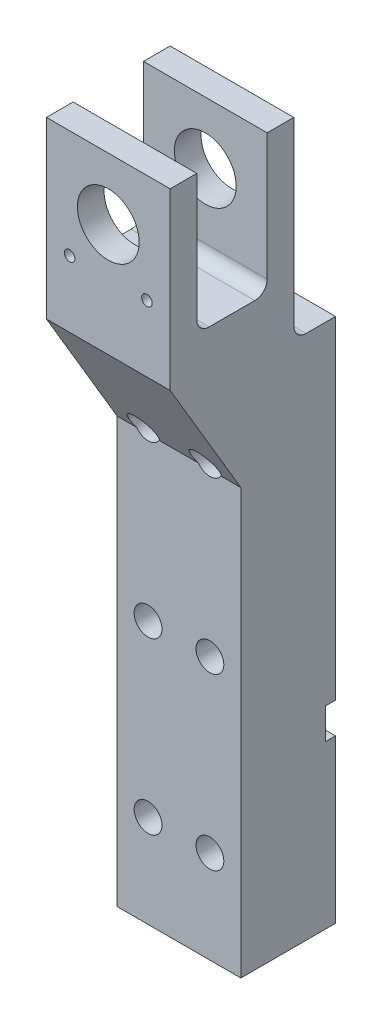
SolidWorks part; units mm, degrees
ref_plane "前视基准面" through (0, 0, 0) normal (0, 0, 1) x (1, 0, 0)
ref_plane "上视基准面" through (0, 0, 0) normal (0, 1, 0) x (1, 0, 0)
ref_plane "右视基准面" through (0, 0, 0) normal (1, 0, 0) x (0, 0, -1)
sketch "草图1" plane through (0, 0, 0) normal (0, 0, 1) x (1, 0, 0)
  line L1 (40, -232.5) -> (-40, -232.5)
  line L2 (40, -232.5) -> (40, 232.5)
  line L3 (40, 232.5) -> (-40, 232.5)
  line L4 (-40, -232.5) -> (-40, 232.5)
  line L5 (40, -232.5) -> (-40, 232.5) construction
  line L6 (40, 232.5) -> (-40, -232.5) construction
  point P0 (0, 0)
  dimension "D1" = 80
  dimension "D2" = 465
extrude "凸台-拉伸1" add sketch "草图1" along normal blind 107
sketch "草图2" plane through (-40, 0, 0) normal (-1, 0, 0) x (0, 0, 1)
  line L0 (27, 232.5) -> (27, 115.5)
  line L1 (107, 232.5) -> (0, 232.5) construction
  line L2 (19, 107.5) -> (0, 107.5)
  line L3 (0, 232.5) -> (0, -232.5) construction
  line L4 (0, 107.5) -> (0, 232.5)
  line L5 (0, 232.5) -> (27, 232.5)
  line L6 (107, 232.5) -> (107, -232.5) construction
  line L7 (44.25, 232.5) -> (44.25, 142.5)
  line L8 (44.25, 142.5) -> (89.75, 142.5)
  line L9 (89.75, 142.5) -> (89.75, 232.5)
  line L10 (89.75, 232.5) -> (44.25, 232.5)
  line L11 (27, 232.5) -> (107, 232.5) construction
  line L12 (67, 232.5) -> (67, 78.872) construction
  arc A0 (27, 115.5) -> (19, 107.5) centre (19, 115.5) cw
  dimension "D3" = 8
  dimension "D1" = 125
  dimension "D2" = 80
  dimension "D4" = 45.5
  dimension "D5" = 90
extrude "切除-拉伸1" cut sketch "草图2" against normal up to next
sketch "草图3" plane through (-40, 0, 0) normal (-1, 0, 0) x (0, 0, 1)
  line L0 (107, 119.5307) -> (61.2772, 42.3119)
  line L1 (107, 232.5) -> (107, -232.5) construction
  line L2 (61.2772, 42.3119) -> (61.2772, -232.5)
  line L3 (107, -232.5) -> (0, -232.5) construction
  line L4 (61.2772, -232.5) -> (107, -232.5)
  line L5 (107, -232.5) -> (107, 119.5307)
extrude "切除-拉伸2" cut sketch "草图3" against normal up to next
sketch "草图4" plane through (0, 0, 107) normal (0, 0, 1) x (1, 0, 0)
  line L0 (0, 232.5) -> (0, 119.5307) construction
  line L1 (40, 232.5) -> (-40, 232.5) construction
  line L2 (40, 119.5307) -> (-40, 119.5307) construction
  circle A0 centre (0, 192.5) radius 20
  dimension "D1" = 40
  dimension "D2" = 40
extrude "切除-拉伸3" cut sketch "草图4" against normal up to surface (80 mm away) up to face at (0, 174, 27)
hole_wizard "M8 螺纹孔1" positions "草图6" profile "草图7" tap size "M8" standard "GB"
sketch "草图6" plane through (0, 0, 107) normal (0, 0, 1) x (1, 0, 0)
  line L0 (0, 192.5) -> (0, 153.2321) construction
  point P0 (-25, 162.5)
  point P2 (25, 162.5)
  point P10 (0, 0)
  dimension "D1" = 50
  dimension "D2" = 30
sketch "草图7" plane through (-25, 162.5, 107) normal (1, 0, 0) x (0, -1, 0)
  line L0 (0, 0) -> (0, 17.25)
  line L1 (0, 17.25) -> (3.4, 17.25)
  line L2 (3.4, 17.25) -> (3.4, 0)
  line L5 (3.4, 0) -> (0, 0)
  line L11 (0, -6.35) -> (0, 107.95) construction
  dimension "通孔螺纹孔钻头直径" = 6.8
  dimension "通孔螺纹孔钻头深度" = 17.25
cosmetic thread "孔螺蚊线1" parameters "D2"=8
cosmetic thread "孔螺蚊线2" parameters "D2"=8
sketch "草图8" plane through (0, 0, 0) normal (0, 0, -1) x (-1, 0, 0)
  line L0 (0, 0) -> (0, 93.2983) construction
  line L1 (0, 192.5) -> (-90.5087, 192.5) construction
  circle A0 centre (-20, 47.5) radius 9
  dimension "D1" = 18
  dimension "D3" = 145
  dimension "D2" = 40
extrude "切除-拉伸4" cut sketch "草图8" against normal up to next
pattern_linear "阵列(线性)1" count 2 spacing 40 along (-1, 0, 0) count 3 spacing 110 along (0, -1, 0) of "切除-拉伸4"
sketch "草图9" plane through (0, 0, 0) normal (0, 0, -1) x (-1, 0, 0)
  line L0 (-40, -107.5) -> (40, -107.5)
  line L1 (-40, -232.5) -> (-40, 107.5) construction
  line L2 (40, 107.5) -> (40, -232.5) construction
  line L3 (40, -107.5) -> (40, -127.5)
  line L4 (40, -127.5) -> (-40, -127.5)
  line L5 (-40, -127.5) -> (-40, -107.5)
  line L6 (-40, -117.5) -> (40, -117.5) construction
  circle A0 centre (-20, -62.5) radius 9 construction
  dimension "D1" = 20
  dimension "D2" = 55
extrude "切除-拉伸5" cut sketch "草图9" against normal blind 6.5
hole_wizard "M8 螺纹孔2" positions "草图11" profile "草图12" tap size "M8" standard "GB"
sketch "草图11" plane through (0, 0, 6.5) normal (0, 0, -1) x (-1, 0, 0)
  line L0 (0, -127.5) -> (0, -107.5) construction
  line L1 (-40, -127.5) -> (40, -127.5) construction
  line L2 (40, -107.5) -> (-40, -107.5) construction
  point P0 (-20, -117.5)
  point P2 (20, -117.5)
  point P14 (-20, -121.2588)
  point P15 (-20, -115.8121)
  point P16 (0, 0)
  point P17 (0, -117.5)
  point P18 (0, 0)
  point P19 (0, 0)
  dimension "D1" = 40
sketch "草图12" plane through (20, -117.5, 6.5) normal (1, 0, 0) x (0, 1, 0)
  line L0 (0, 0) -> (0, 27.0429)
  line L1 (0, 27.0429) -> (3.4, 25)
  line L2 (3.4, 25) -> (3.4, 0)
  line L5 (3.4, 0) -> (0, 0)
  line L10 (0, 27.0429) -> (-3.4, 25) construction
  line L11 (0, -6.35) -> (0, 107.95) construction
  dimension "螺纹孔钻头直径" = 6.8
  dimension "螺纹孔钻头深度" = 25
  dimension "导头角度" = 118
cosmetic thread "孔螺蚊线3" parameters "D1"=25, "D2"=8
cosmetic thread "孔螺蚊线4" parameters "D1"=25, "D2"=8
fillet "圆角1" radius 8 2 edges at (0, 142.5, 89.75) (0, 142.5, 44.25)
